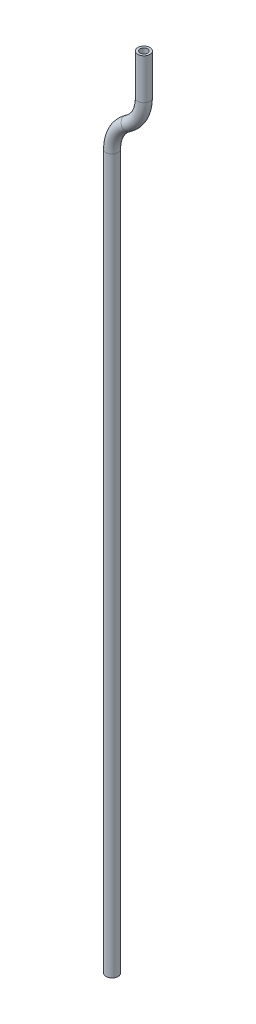
SolidWorks part; units mm, degrees
ref_plane "Front Plane" through (0, 0, 0) normal (0, 0, 1) x (1, 0, 0)
ref_plane "Top Plane" through (0, 0, 0) normal (0, 1, 0) x (1, 0, 0)
ref_plane "Right Plane" through (0, 0, 0) normal (1, 0, 0) x (0, 0, -1)
sketch "Illustrative smooth utility route" plane through (0, 0, 0) normal (0, 0, 1) x (1, 0, 0)
  line L0 (13.55, 0) -> (13.55, -13.5)
  line L1 (3, -33.5) -> (3, -270.5)
  arc A0 (13.55, -13.5) -> (8.275, -23.5) centre (1.4338, -13.5) cw
  arc A1 (8.275, -23.5) -> (3, -33.5) centre (15.1162, -33.5) ccw
sketch "Utility circular cross section" plane through (0, 0, 0) normal (0, 1, 0) x (1, 0, 0)
  circle A0 centre (13.55, 0) radius 2
  circle A1 centre (13.55, 0) radius 1.25
sweep "Native hollow utility sweep" add profiles "Utility circular cross section" path "Illustrative smooth utility route"
